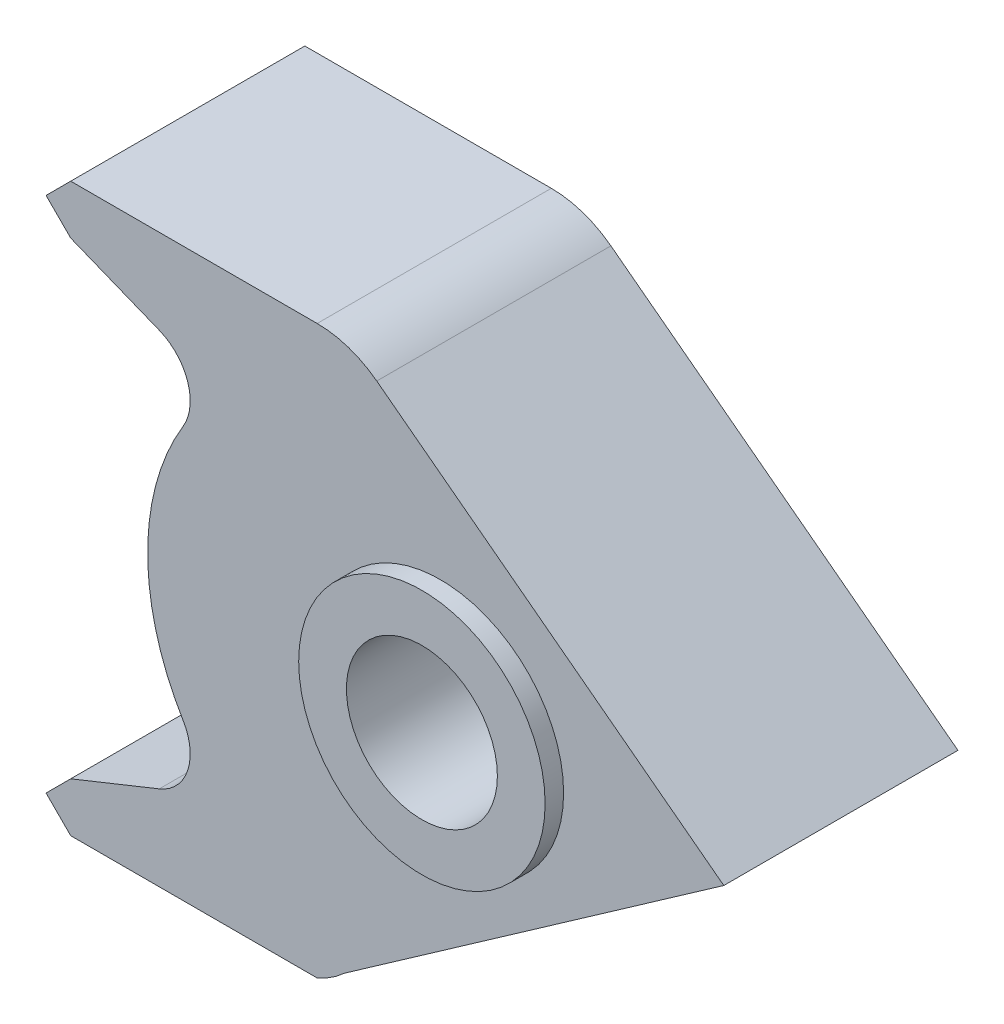
SolidWorks part; units mm, degrees
ref_plane "Plano frontal" through (0, 0, 0) normal (0, 0, 1) x (1, 0, 0)
ref_plane "Plano superior" through (0, 0, 0) normal (0, 1, 0) x (1, 0, 0)
ref_plane "Plano direito" through (0, 0, 0) normal (1, 0, 0) x (0, 0, -1)
sketch "Esboço1" plane through (0, 0, 0) normal (0, 0, 1) x (1, 0, 0)
  line L1 (0, 0) -> (-28.1639, 21.3728)
  line L2 (-33, 23) -> (-53, 23)
  line L3 (-53, 23) -> (-55, 21)
  line L4 (-55, 21) -> (-53, 19)
  line L5 (-53, 19) -> (-45.812, 16.1148)
  line L6 (-53, -19) -> (-45.812, -16.1148)
  line L7 (-55, -21) -> (-53, -19)
  line L8 (-53, -23) -> (-55, -21)
  line L9 (-33, -23) -> (-53, -23)
  line L10 (0, 0) -> (-30.7812, -21.5532)
  line L11 (0, 0) -> (87.2743, 0)
  circle A0 centre (-23, 0) radius 6.125
  arc A1 (-28.1639, 21.3728) -> (-33, 23) centre (-33, 15) ccw
  arc A2 (-43.8776, 10.3356) -> (-43.8776, -10.3356) centre (-26.7552, 0) ccw
  arc A3 (-45.812, 16.1148) -> (-43.8776, 10.3356) centre (-47.302, 12.4027) cw
  arc A5 (-45.812, -16.1148) -> (-43.8776, -10.3356) centre (-47.302, -12.4027) ccw
  arc A6 (-30.7812, -21.5532) -> (-33, -23) centre (-36.1999, -15.6678) cw
  point P11 (-30.3082, 23)
  point P19 (-40.8973, 14.1421)
  point P28 (-43.2671, -14.1421)
  point P29 (-32.8474, -23)
  dimension "D1" = 12.25
  dimension "D5" = 8
  dimension "D8" = 20
  dimension "D9" = 4
  dimension "D2" = 55
  dimension "D3" = 23
  dimension "D6" = 90
  dimension "D7" = 4
  dimension "D10" = 20
extrude "Ressalto-extrusão1" add sketch "Esboço1" along normal blind 22 contours A6 L10 L1 A1 L2 L3 L4 L5 A3 A2 A5 L6 L7 L8 L9 A0
sketch "Esboço2" plane through (0, 0, 22) normal (0, 0, 1) x (1, 0, 0)
  circle A0 centre (-23, 0) radius 10
  dimension "D1" = 20
extrude "Corte-extrusão1" cut sketch "Esboço2" against normal blind 1.5 flip side to cut
sketch "Esboço3" plane through (0, 0, 0) normal (0, 0, -1) x (-1, 0, 0)
  circle A0 centre (23, 0) radius 10
  dimension "D1" = 20
extrude "Corte-extrusão2" cut sketch "Esboço3" against normal blind 1.5 flip side to cut
